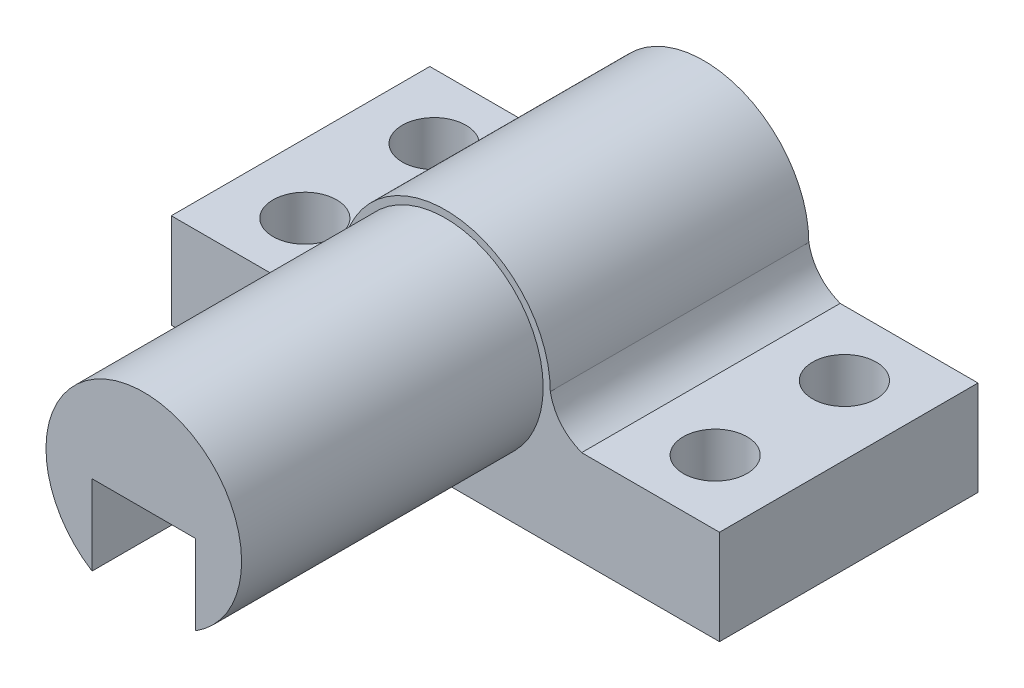
SolidWorks part; units mm, degrees
ref_plane "Front Plane" through (0, 0, 0) normal (0, 0, 1) x (1, 0, 0)
ref_plane "Top Plane" through (0, 0, 0) normal (0, 1, 0) x (1, 0, 0)
ref_plane "Right Plane" through (0, 0, 0) normal (1, 0, 0) x (0, 0, -1)
sketch "Sketch1" plane through (0, 0, 0) normal (0, 0, 1) x (1, 0, 0)
  line L0 (0, 0) -> (0, 12.175) construction
  line L1 (0, 12.175) -> (0, -15.3237) construction
  line L2 (-31.8086, -15.3237) -> (31.8086, -15.3237)
  line L3 (31.8086, -15.3237) -> (31.8086, -4.3237)
  line L4 (31.8086, -4.3237) -> (15.8086, -4.3237)
  line L5 (-31.8086, -15.3237) -> (-31.8086, -4.3237)
  line L6 (-31.8086, -4.3237) -> (-15.8086, -4.3237)
  arc A0 (12.175, 0) -> (-12.175, 0) centre (0, 0) ccw
  spline S0 degree 2 poles (12.175, 0) (12.801, -3.0839) (15.8086, -4.3237) knots 0 0 0 1 1 1
  spline S1 degree 2 poles (-12.175, 0) (-12.801, -3.0839) (-15.8086, -4.3237) knots 0 0 0 1 1 1
  dimension "D1" = 16
  dimension "D2" = 11
extrude "Boss-Extrude1" add sketch "Sketch1" along normal blind 30
sketch "Sketch2" plane through (0, 0, 30) normal (0, 0, 1) x (1, 0, 0)
  circle A0 centre (0, 0) radius 11.35
extrude "Boss-Extrude2" add sketch "Sketch2" along normal blind 35
sketch "Sketch3" plane through (0, -4.3237, 0) normal (0, 1, 0) x (1, 0, 0)
  line L0 (-31.8086, -15) -> (31.8086, -15) construction
  line L1 (-31.8086, -30) -> (-31.8086, 0) construction
  line L2 (31.8086, -30) -> (31.8086, 0) construction
  line L3 (-23.8086, 0) -> (-23.8086, -30) construction
  line L4 (-15.8086, 0) -> (-31.8086, 0) construction
  line L5 (-15.8086, -30) -> (-31.8086, -30) construction
  line L6 (23.8086, 0) -> (23.8086, -30) construction
  line L7 (31.8086, 0) -> (15.8086, 0) construction
  line L8 (31.8086, -30) -> (15.8086, -30) construction
  line L9 (0, 0) -> (0, -39.3896) construction
  line L11 (-27.0651, -7.5) -> (31.8086, -7.5) construction
  line L12 (-27.0651, -22.5) -> (31.8086, -22.5) construction
  circle A0 centre (-23.8086, -7.5) radius 3.7
  circle A1 centre (-23.8086, -22.5) radius 3.7
  circle A2 centre (23.8086, -22.5) radius 3.7
  circle A3 centre (23.8086, -7.5) radius 3.7
extrude "Cut-Extrude1" cut sketch "Sketch3" against normal through all
sketch "Sketch5" plane through (0, 0, 65) normal (0, 0, 1) x (1, 0, 0)
  line L0 (-3.75, -11.35) -> (3.75, -11.35)
  line L1 (0, -11.35) -> (0, -6.4237) construction
  line L3 (-6, -0.35) -> (6, -0.35)
  line L4 (6, -0.35) -> (6, -11.35)
  line L5 (6, -11.35) -> (3.75, -11.35)
  line L6 (-6, -11.35) -> (-3.75, -11.35)
  line L7 (-6, -0.35) -> (-6, -11.35)
  circle A0 centre (0, 0) radius 11.35 construction
  circle A1 centre (0, 0) radius 11.35 construction
extrude "Cut-Extrude2" cut sketch "Sketch5" against normal blind 28
